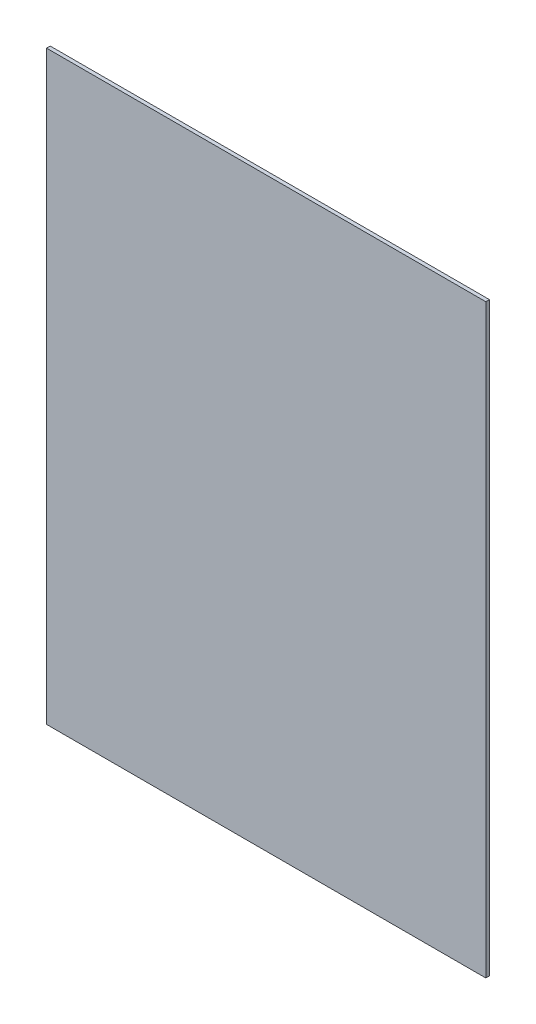
SolidWorks part; units mm, degrees
material "Sosna"
ref_plane "Płaszczyzna przednia" through (0, 0, 0) normal (0, 0, 1) x (1, 0, 0)
ref_plane "Płaszczyzna górna" through (0, 0, 0) normal (0, 1, 0) x (1, 0, 0)
ref_plane "Płaszczyzna prawa" through (0, 0, 0) normal (1, 0, 0) x (0, 0, -1)
sketch "Szkic1" plane through (0, 0, 0) normal (0, 0, 1) x (1, 0, 0)
  line L1 (0, 0) -> (600, 0)
  line L2 (0, 0) -> (0, 800)
  line L3 (0, 800) -> (600, 800)
  line L4 (600, 0) -> (600, 800)
  dimension "D1" = 600
  dimension "D2" = 800
extrude "Dodanie-wyciągnięcie1" add sketch "Szkic1" along normal blind 5
